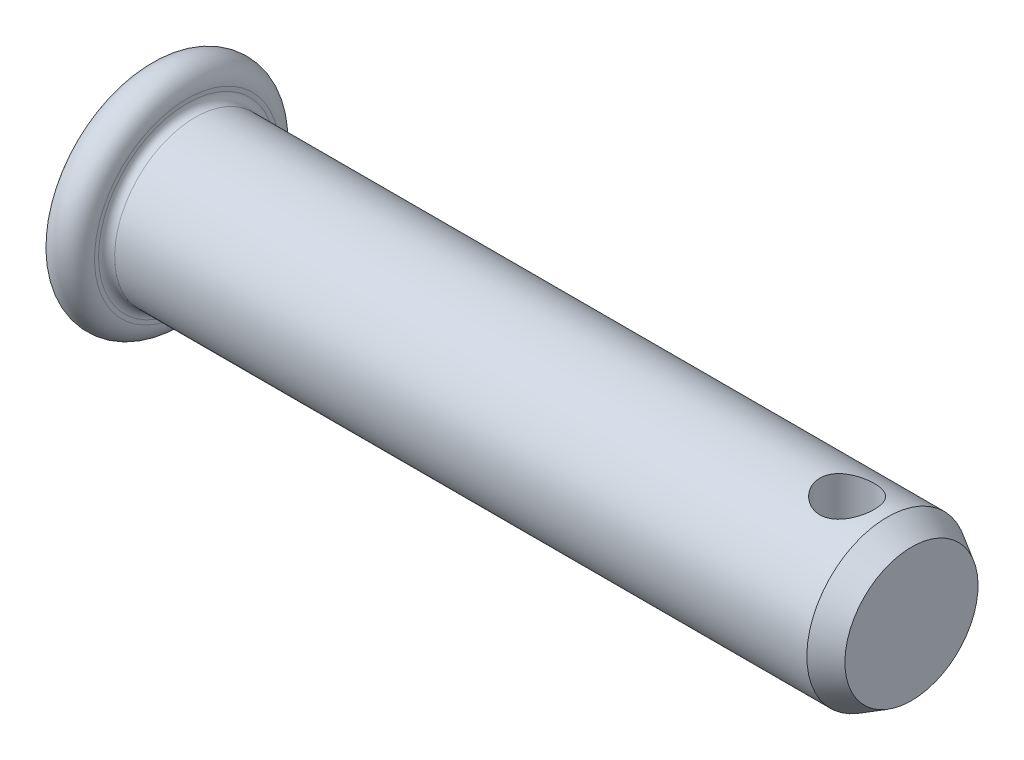
SolidWorks part; units mm, degrees
ref_plane "Front" through (0, 0, 0) normal (0, 0, 1) x (1, 0, 0)
ref_plane "Top" through (0, 0, 0) normal (0, 1, 0) x (1, 0, 0)
ref_plane "Right" through (0, 0, 0) normal (1, 0, 0) x (0, 0, -1)
other "Configuration Table"
sketch "Sketch1" plane through (0, 0, 0) normal (0, 0, 1) x (1, 0, 0)
  line L0 (47.5, 0) -> (0, 0)
  line L1 (0, 0) -> (0, 5.75)
  line L2 (47.5, 0) -> (47.5, 4.134)
  line L3 (47.5, 4.134) -> (46, 5)
  line L4 (46, 5) -> (2.5, 5)
  line L5 (2.5, 5) -> (2.5, 5.75)
  line L6 (-19.83, 0) -> (9.2989, 0) construction
  arc A0 (0, 5.75) -> (2.5, 5.75) centre (1.25, 5.75) cw
  dimension "l" = 45
  dimension "k" = 2.5
  dimension "d" = 10
  dimension "D4" = 30
  dimension "c" = 1.5
  dimension "dk" = 14
revolve "BaseBody" add sketch "Sketch1" angle 360 about L6
fillet "Chamfer1" radius 0.5 1 edges at (2.5, -5, 0)
sketch "Sketch2" plane through (0, 0, 0) normal (0, 1, 0) x (1, 0, 0)
  line L0 (-19.83, 0) -> (9.2989, 0) construction
  line L1 (47.5, -4.134) -> (47.5, 4.134) construction
  circle A0 centre (43.5, 0) radius 1.69
  dimension "D2" = 4
  dimension "d1" = 3.38
extrude "Hole" cut sketch "Sketch2" against normal through all and the other way through all
